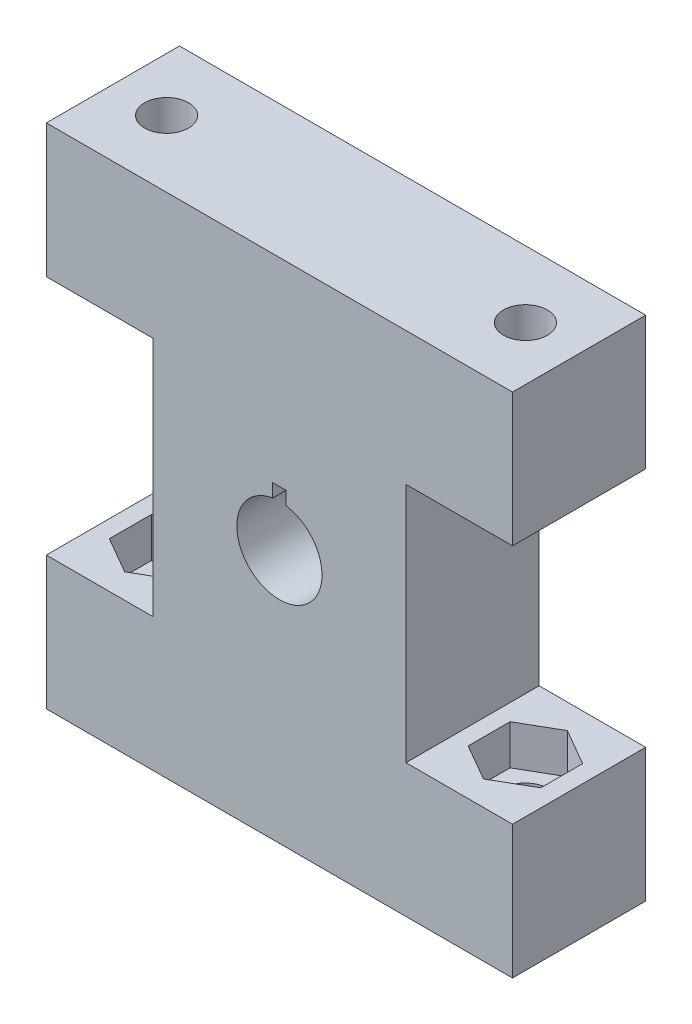
SolidWorks part; units mm, degrees
ref_plane "Front Plane" through (0, 0, 0) normal (0, 0, 1) x (1, 0, 0)
ref_plane "Top Plane" through (0, 0, 0) normal (0, 1, 0) x (1, 0, 0)
ref_plane "Right Plane" through (0, 0, 0) normal (1, 0, 0) x (0, 0, -1)
sketch "Sketch1" plane through (0, 0, 0) normal (0, 0, 1) x (1, 0, 0)
  line L1 (-17.5, 19.05) -> (17.5, 19.05)
  line L2 (-17.5, 19.05) -> (-17.5, -19.05)
  line L3 (-17.5, -19.05) -> (17.5, -19.05)
  line L4 (17.5, 19.05) -> (17.5, -19.05)
  point P4 (0, 19.05)
  point P6 (-17.5, 0)
  dimension "D1" = 38.1
  dimension "D2" = 35
extrude "Boss-Extrude1" add sketch "Sketch1" along normal blind 10
hole_wizard "Ø3.3 (3.3) Diameter Hole1" positions "Sketch2" profile "Sketch3" hole size "Ø3.3" standard "ANSI Metric" end condition through all
sketch "Sketch2" plane through (0, 19.05, 0) normal (0, 1, 0) x (1, 0, 0)
  line L0 (-17.5, -10) -> (-17.5, 0) construction
  line L1 (-13.47, -5) -> (13.47, -5) construction
  point P0 (-13.47, -5)
  point P2 (13.47, -5)
  point P7 (-17.5, -5)
  point P12 (0, -5)
  dimension "D1" = 26.94
sketch "Sketch3" plane through (-13.47, 19.05, 5) normal (1, 0, 0) x (0, 0, 1)
  line L0 (0, 0) -> (0, 38.1)
  line L1 (0, 38.1) -> (1.65, 38.1)
  line L2 (1.65, 38.1) -> (1.65, 0)
  line L5 (1.65, 0) -> (0, 0)
  line L11 (0, -6.35) -> (0, 107.95) construction
  dimension "Thru Hole Dia." = 3.3
  dimension "Thru Hole Depth" = 38.1
sketch "Sketch4" plane through (0, 0, 10) normal (0, 0, 1) x (1, 0, 0)
  line L0 (-17.5, -19.05) -> (17.5, -19.05) construction
  line L1 (17.5, 19.05) -> (-17.5, 19.05) construction
  circle A0 centre (0, 0) radius 3.2
  point P8 (0, 19.05)
  dimension "D1" = 6.4
  dimension "D2" = 19.05
extrude "Cut-Extrude1" cut sketch "Sketch4" against normal through all
sketch "Sketch5" plane through (0, 0, 0) normal (0, 0, -1) x (-1, 0, 0)
  line L0 (-17.5, -19.05) -> (-17.5, 19.05) construction
  line L1 (-17.5, 9.05) -> (-9.5, 9.05)
  line L2 (-17.5, 9.05) -> (-17.5, 0)
  line L3 (-17.5, 0) -> (-9.5, 0)
  line L4 (-9.5, 9.05) -> (-9.5, 0)
  line L5 (-17.5, 19.05) -> (17.5, 19.05) construction
  dimension "D1" = 10
  dimension "D2" = 8
extrude "Cut-Extrude2" cut sketch "Sketch5" against normal blind 10
sketch "Sketch6" plane through (0, 9.05, 0) normal (0, -1, 0) x (1, 0, 0)
  line L0 (17.5, 10) -> (17.5, 0) construction
  line L1 (16.195, 6.5733) -> (13.47, 8.1466)
  line L2 (13.47, 8.1466) -> (10.745, 6.5733)
  line L3 (10.745, 6.5733) -> (10.745, 3.4267)
  line L4 (10.745, 3.4267) -> (13.47, 1.8534)
  line L5 (13.47, 1.8534) -> (16.195, 3.4267)
  line L6 (16.195, 3.4267) -> (16.195, 6.5733)
  circle A0 centre (13.47, 5) radius 2.725 construction
  dimension "D1" = 5.45
extrude "Cut-Extrude3" cut sketch "Sketch6" against normal blind 3
mirror "Mirror2" about plane through (0, 0, 0) normal (1, 0, 0) of "Cut-Extrude3", "Cut-Extrude2" second plane through (0, 0, 0) second plane normal (0, 1, 0)
sketch "Sketch7" plane through (0, 0, 10) normal (0, 0, 1) x (1, 0, 0)
  line L1 (-0.5, 4.1607) -> (0.5, 4.1607)
  line L2 (-0.5, 4.1607) -> (-0.5, 3.1607)
  line L3 (-0.5, 3.1607) -> (0.5, 3.1607)
  line L4 (0.5, 4.1607) -> (0.5, 3.1607)
  circle A0 centre (0, 0) radius 3.2 construction
  point P4 (0, 3.1607)
  point P6 (0, 0)
  dimension "D1" = 1
  dimension "D2" = 1
extrude "Cut-Extrude4" cut sketch "Sketch7" against normal through all both and the other way through all
